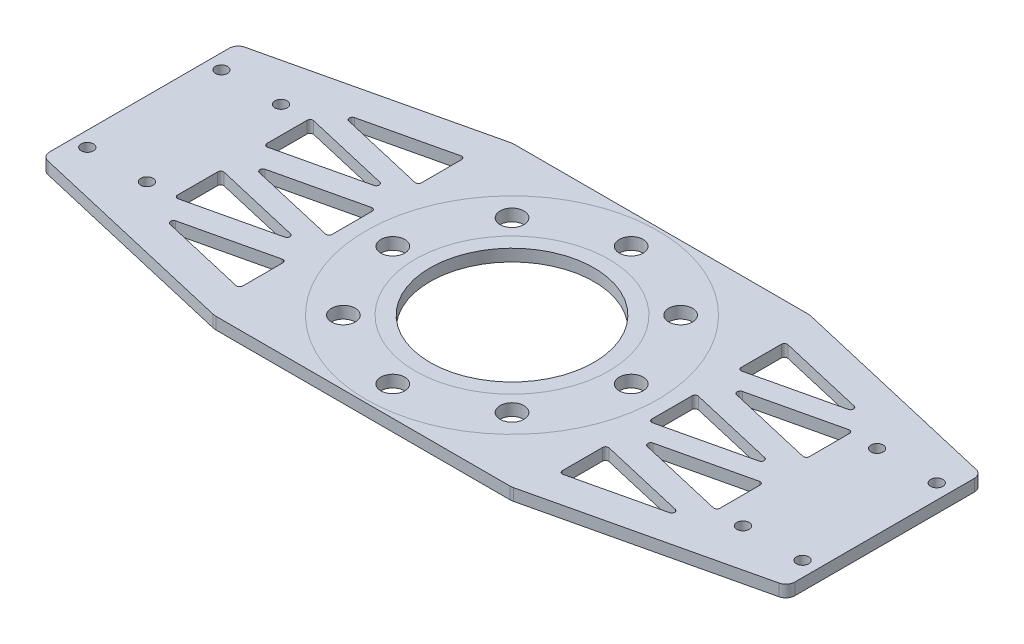
SolidWorks part; units mm, degrees
material "A-玻璃纤维"
ref_plane "前视基准面" through (0, 0, 0) normal (0, 0, 1) x (1, 0, 0)
ref_plane "上视基准面" through (0, 0, 0) normal (0, 1, 0) x (1, 0, 0)
ref_plane "右视基准面" through (0, 0, 0) normal (1, 0, 0) x (0, 0, -1)
sketch "草图1" plane through (0, 0, 0) normal (0, 1, 0) x (1, 0, 0)
  line L0 (-125, -50) -> (125, 50) construction
  line L1 (-125, 50) -> (125, 50)
  line L2 (-125, 50) -> (-125, -50)
  line L3 (-125, -50) -> (125, -50)
  line L4 (125, 50) -> (125, -50)
  line L5 (0, -50) -> (0, 50) construction
  line L6 (-125, 0) -> (125, 0) construction
  line L7 (-125, 32.5) -> (-13.6064, 58.4368)
  line L8 (0, 0) -> (125, -50) construction
  line L9 (-125, -32.5) -> (-13.6064, -58.4368)
  line L10 (125, 32.5) -> (13.6064, 58.4368)
  line L11 (125, -32.5) -> (13.6064, -58.4368)
  line L13 (-120, 22.5) -> (-100, 22.5) construction
  line L14 (-120, 22.5) -> (-120, -22.5) construction
  line L15 (-120, -22.5) -> (-100, -22.5) construction
  line L16 (-100, 22.5) -> (-100, -22.5) construction
  line L17 (-120, 22.5) -> (-100, -22.5) construction
  line L18 (-120, -22.5) -> (-100, 22.5) construction
  circle A0 centre (0, 0) radius 40 construction
  circle A1 centre (0, 40) radius 4
  circle A2 centre (28.2843, 28.2843) radius 4
  circle A3 centre (40, 0) radius 4
  circle A4 centre (28.2843, -28.2843) radius 4
  circle A5 centre (0, -40) radius 4
  circle A6 centre (-28.2843, -28.2843) radius 4
  circle A7 centre (-40, 0) radius 4
  circle A8 centre (-28.2843, 28.2843) radius 4
  circle A17 centre (0, 0) radius 60
  circle A18 centre (-120, 22.5) radius 2.05
  circle A19 centre (-100, 22.5) radius 2.05
  circle A20 centre (-120, -22.5) radius 2.05
  circle A21 centre (-100, -22.5) radius 2.05
  circle A22 centre (100, 22.5) radius 2.05
  circle A23 centre (100, -22.5) radius 2.05
  circle A24 centre (120, -22.5) radius 2.05
  circle A25 centre (120, 22.5) radius 2.05
  point P10 (-110, 0)
  point P27 (0, 0)
  point P67 (0, 0)
  dimension "D1" = 80
  dimension "D4" = 8
  dimension "D7" = 110
  dimension "D8" = 20
  dimension "D6" = 4.1
  dimension "D9" = 120
  dimension "D2" = 250
  dimension "D3" = 100
  dimension "D10" = 65
  dimension "D11" = 45
  dimension "D5" = 8
extrude "凸台-拉伸1" add sketch "草图1" along normal blind 4
sketch "草图2" plane through (0, 4, 0) normal (0, 1, 0) x (1, 0, 0)
  circle A0 centre (0, 0) radius 49
  circle A1 centre (0, 0) radius 32.5
  dimension "D1" = 98
  dimension "D2" = 65
split line "分割线1"
sketch "草图5" plane through (0, 4, 0) normal (0, 1, 0) x (1, 0, 0)
  circle A0 centre (0, 0) radius 27.5
  dimension "D1" = 55
extrude "切除-拉伸5" cut sketch "草图5" against normal blind 10
fillet "圆角2" radius 3 4 edges at (125, 2, -32.5) (125, 2, 32.5) (-125, 2, 32.5) (-125, 2, -32.5)
fillet "圆角3" radius 5 4 edges at (49.841, 2, 50) (-49.841, 2, 50) (-49.841, 2, -50) (49.841, 2, -50)
sketch "草图6" plane through (0, 4, 0) normal (0, 1, 0) x (1, 0, 0)
  line L0 (-88, 30) -> (-53.6416, 38)
  line L1 (-53.6416, 38) -> (-53.6416, 22)
  line L2 (-53.6416, 22) -> (-88, 30)
  line L3 (-122.6803, 33.0401) -> (-50.4005, 49.8697) construction
  line L4 (-125, 30.1183) -> (-125, -30.1183) construction
  line L5 (-53.6416, -8) -> (-88, 0)
  line L6 (-88, 0) -> (-53.6416, 8)
  line L7 (-53.6416, 8) -> (-53.6416, -8)
  line L8 (-53.6416, -38) -> (-88, -30)
  line L9 (-88, -30) -> (-53.6416, -22)
  line L10 (-53.6416, -22) -> (-53.6416, -38)
  line L11 (-91, 23.5113) -> (-91, 7.5113)
  line L12 (-91, 7.5113) -> (-56.6416, 15.5113)
  line L13 (-56.6416, 15.5113) -> (-91, 23.5113)
  line L14 (-56.6416, -14.4887) -> (-91, -6.4887)
  line L15 (-91, -6.4887) -> (-91, -22.4887)
  line L16 (-91, -22.4887) -> (-56.6416, -14.4887)
  line L17 (0, 21.9097) -> (0, -24.1481) construction
  line L18 (53.6416, -22) -> (53.6416, -38)
  line L19 (88, -30) -> (53.6416, -22)
  line L20 (53.6416, -38) -> (88, -30)
  line L21 (91, -22.4887) -> (56.6416, -14.4887)
  line L22 (91, -6.4887) -> (91, -22.4887)
  line L23 (56.6416, -14.4887) -> (91, -6.4887)
  line L24 (91, 7.5113) -> (56.6416, 15.5113)
  line L25 (91, 23.5113) -> (91, 7.5113)
  line L26 (56.6416, 15.5113) -> (91, 23.5113)
  line L27 (53.6416, 8) -> (53.6416, -8)
  line L28 (88, 0) -> (53.6416, 8)
  line L29 (53.6416, -8) -> (88, 0)
  line L30 (53.6416, 38) -> (53.6416, 22)
  line L31 (88, 30) -> (53.6416, 38)
  line L32 (53.6416, 22) -> (88, 30)
  point P5 (-53.6416, 0)
  point P7 (-53.6416, 30)
  point P19 (-91, 15.5113)
  dimension "D1" = 16
  dimension "D2" = 16
  dimension "D3" = 37
  dimension "D5" = 30
  dimension "D6" = 7
  dimension "D7" = 34
  dimension "D9" = 30
  dimension "D4" = 3
  dimension "D8" = 2
extrude "切除-拉伸6" cut sketch "草图6" against normal blind 10
fillet "圆角4" radius 1 30 edges at (-53.6416, 2, -38) (-53.6416, 2, -22) (-88, 2, -30) (53.6416, 2, -22) (53.6416, 2, -38) (88, 2, -30) (56.6416, 2, 14.4887) (91, 2, 6.4887) (91, 2, 22.4887) (53.6416, 2, 38) (53.6416, 2, 22) (88, 2, 30) (53.6416, 2, 8) (53.6416, 2, -8) (88, 2, 0) (56.6416, 2, -15.5113) (91, 2, -23.5113) (91, 2, -7.5113) (-53.6416, 2, 8) (-88, 2, 0) (-53.6416, 2, -8) (-91, 2, -7.5113) (-91, 2, -23.5113) (-56.6416, 2, -15.5113) (-91, 2, 22.4887) (-53.6416, 2, 38) (-88, 2, 30) (-53.6416, 2, 22) (-56.6416, 2, 14.4887) (-91, 2, 6.4887)
